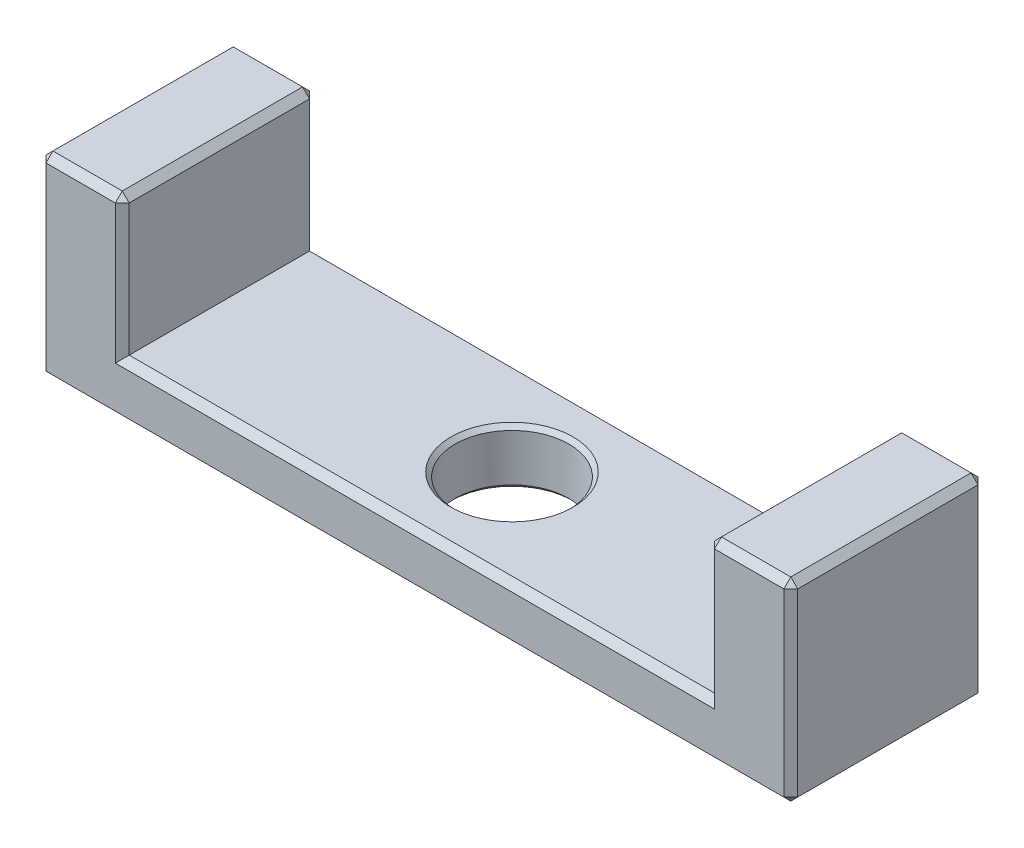
SolidWorks part; units mm, degrees
material "1018 Mild Steel"
ref_plane "Front Plane" through (0, 0, 0) normal (0, 0, 1) x (1, 0, 0)
ref_plane "Top Plane" through (0, 0, 0) normal (0, 1, 0) x (1, 0, 0)
ref_plane "Right Plane" through (0, 0, 0) normal (1, 0, 0) x (0, 0, -1)
sketch "Sketch1" plane through (0, 0, 0) normal (0, 0, 1) x (1, 0, 0)
  line L0 (-21.1, 14) -> (-21.1, 4)
  line L1 (-21.1, 4) -> (21.1, 4)
  line L2 (21.1, 4) -> (21.1, 14)
  line L3 (21.1, 14) -> (27.1, 14)
  line L4 (27.1, 14) -> (27.1, 0)
  line L5 (27.1, 0) -> (-27.1, 0)
  line L6 (-27.1, 0) -> (-27.1, 14)
  line L7 (-27.1, 14) -> (-21.1, 14)
  line L8 (0, 0) -> (0, 4) construction
  dimension "D1" = 42.2
  dimension "D2" = 4
  dimension "D3" = 10
  dimension "D4" = 6
extrude "Boss-Extrude1" add sketch "Sketch1" along normal mid plane 14
sketch "Sketch2" plane through (0, 4, 0) normal (0, 1, 0) x (1, 0, 0)
  circle A0 centre (0, 0) radius 4.1
  dimension "D1" = 8.2
extrude "Cut-Extrude1" cut sketch "Sketch2" against normal through all
chamfer "Chamfer1" distance 0.5 angle 45 23 edges at (0, 4, 7) (0, 4, -7) (21.1, 9, 7) (21.1, 4, 0) (21.1, 9, -7) (27.1, 14, 0) (24.1, 14, 7) (21.1, 14, 0) (24.1, 14, -7) (-21.1, 14, 0) (-21.1, 9, 7) (-24.1, 14, 7) (-27.1, 14, 0) (-21.1, 9, -7) (-24.1, 14, -7) (-27.1, 7, -7) (-27.1, 7, 7) (0, 0, -7) (27.1, 7, -7) (27.1, 7, 7) (27.1, 0, 0) (0, 0, 7) (-27.1, 0, 0)
chamfer "Chamfer2" distance 0.3 angle 45 2 edges at (0, 4, 4.1) (0, 0, 4.1)
